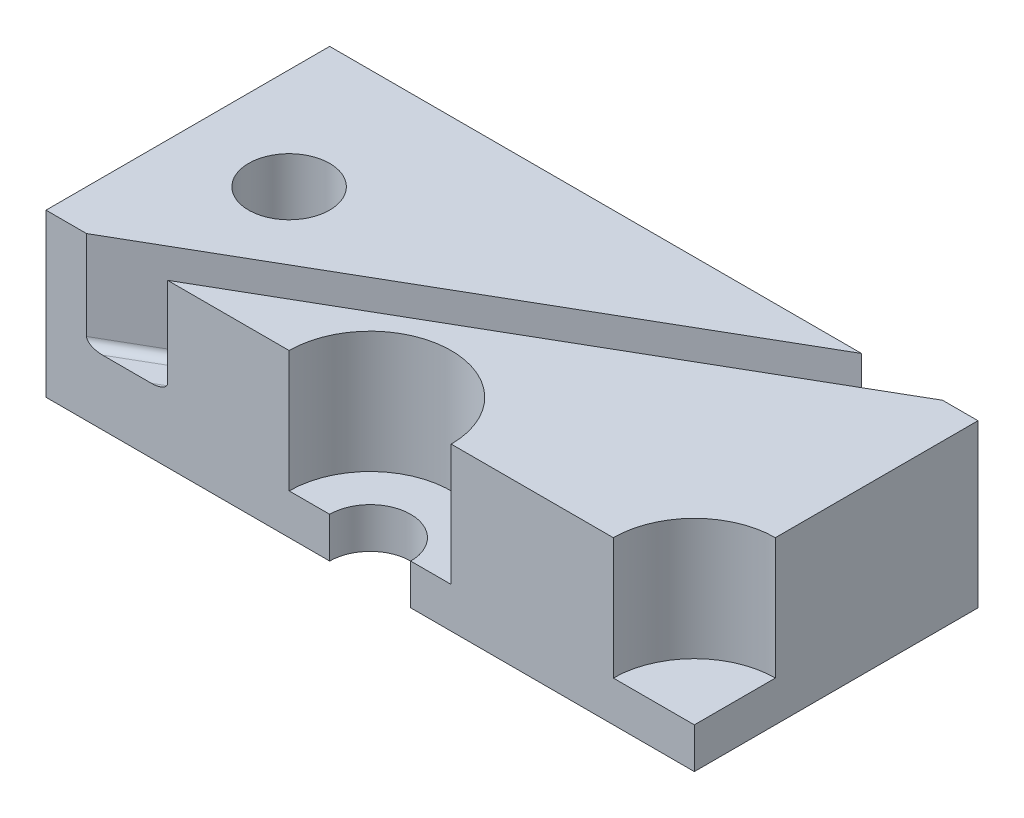
SolidWorks part; units mm, degrees
material "AISI 1020 Steel, Cold Rolled"
ref_plane "Front Plane" through (0, 0, 0) normal (0, 0, 1) x (1, 0, 0)
ref_plane "Top Plane" through (0, 0, 0) normal (0, 1, 0) x (1, 0, 0)
ref_plane "Right Plane" through (0, 0, 0) normal (1, 0, 0) x (0, 0, -1)
sketch "Sketch1" plane through (0, 0, 0) normal (0, 0, 1) x (1, 0, 0)
  line L0 (-82.2036, 33.4719) -> (120.9964, 33.4719)
  line L1 (120.9964, 33.4719) -> (120.9964, 84.2719)
  line L2 (120.9964, 84.2719) -> (-82.2036, 84.2719)
  line L3 (-82.2036, 84.2719) -> (-82.2036, 33.4719)
  dimension "D1" = 203.2
  dimension "D2" = 50.8
  dimension "D3" = 33.4719
  dimension "D4" = 82.2036
extrude "Boss-Extrude1" add sketch "Sketch1" along normal blind 88.9
sketch "Sketch2" plane through (0, 84.2719, 0) normal (0, 1, 0) x (1, 0, 0)
  line L0 (120.9964, -88.9) -> (-82.2036, -88.9) construction
  line L1 (-82.2036, -88.9) -> (-82.2036, 0) construction
  circle A0 centre (-50.4536, -44.45) radius 12.7
  circle A1 centre (19.3964, -88.9) radius 25.4
  circle A2 centre (120.9964, -88.9) radius 25.4
  dimension "D1" = 25.4
  dimension "D2" = 50.8
  dimension "D3" = 50.8
  dimension "D4" = 31.75
  dimension "D5" = 44.45
extrude "Cut-Extrude1" cut sketch "Sketch2" against normal blind 38.1
sketch "Sketch3" plane through (0, 46.1719, 0) normal (0, 1, 0) x (1, 0, 0)
  line L0 (44.7964, -88.9) -> (-6.0036, -88.9) construction
  circle A0 centre (19.3964, -88.9) radius 12.7
  dimension "D1" = 25.4
extrude "Cut-Extrude2" cut sketch "Sketch3" against normal through all
sketch "Sketch4" plane through (0, 84.2719, 0) normal (0, 1, 0) x (1, 0, 0)
  line L0 (-69.5036, -88.9) -> (84.4757, 0)
  line L1 (-6.0036, -88.9) -> (-82.2036, -88.9) construction
  line L2 (120.9964, 0) -> (-82.2036, 0) construction
  line L3 (84.4757, 0) -> (109.8757, 0)
  line L4 (109.8757, 0) -> (-44.1036, -88.9)
  line L5 (-44.1036, -88.9) -> (-69.5036, -88.9)
  line L6 (95.5964, -88.9) -> (44.7964, -88.9) construction
  dimension "D1" = 12.7
  dimension "D2" = 38.1
  dimension "D3" = 30
extrude "Cut-Extrude3" cut sketch "Sketch4" against normal blind 30.48
fillet "Fillet1" radius 2.54 2 edges at (32.886, 53.7919, 44.45) (7.486, 53.7919, 44.45)
